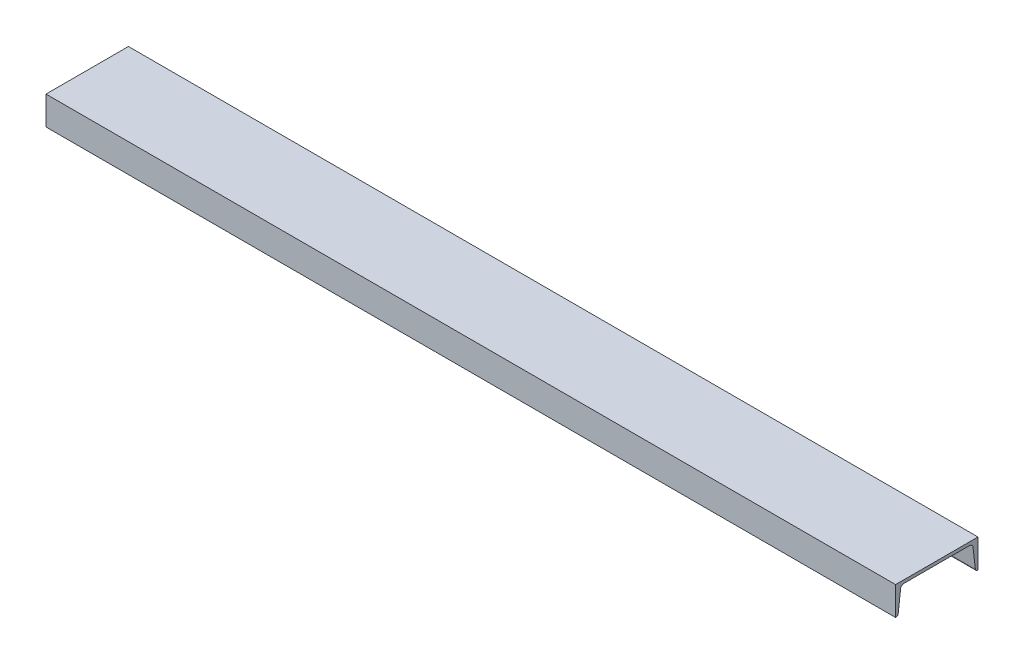
SolidWorks part; units mm, degrees
ref_plane "Спереди" through (0, 0, 0) normal (0, 0, 1) x (1, 0, 0)
ref_plane "Сверху" through (0, 0, 0) normal (0, 1, 0) x (1, 0, 0)
ref_plane "Справа" through (0, 0, 0) normal (1, 0, 0) x (0, 0, -1)
sketch "Эскиз2" plane through (0, 0, 0) normal (1, 0, 0) x (0, 0, -1)
  line L0 (130, 0) -> (-130, 0)
  line L1 (-130, 0) -> (-130, -90)
  line L2 (0, 0) -> (0, -100) construction
  line L3 (101.8373, -10) -> (-101.8373, -10)
  line L4 (-113.796, -16.7206) -> (-121.7267, -83.8216)
  line L5 (-130, -90) -> (-128.6783, -90)
  line L6 (130, -90) -> (128.6783, -90)
  line L7 (113.796, -16.7206) -> (121.7267, -83.8216)
  line L8 (130, 0) -> (130, -90)
  arc A0 (-101.8373, -10) -> (-113.796, -16.7206) centre (-101.8373, -24) ccw
  arc A1 (-128.6783, -90) -> (-121.7267, -83.8216) centre (-128.6783, -83) ccw
  arc A2 (128.6783, -90) -> (121.7267, -83.8216) centre (128.6783, -83) cw
  arc A3 (101.8373, -10) -> (113.796, -16.7206) centre (101.8373, -24) cw
  point P19 (0, -10)
extrude "Бобышка-Вытянуть1" add sketch "Эскиз2" along normal blind 2680 contours L0 L1 L5 A1 L4 A0 L3 A3 L7 A2 L6 L8
